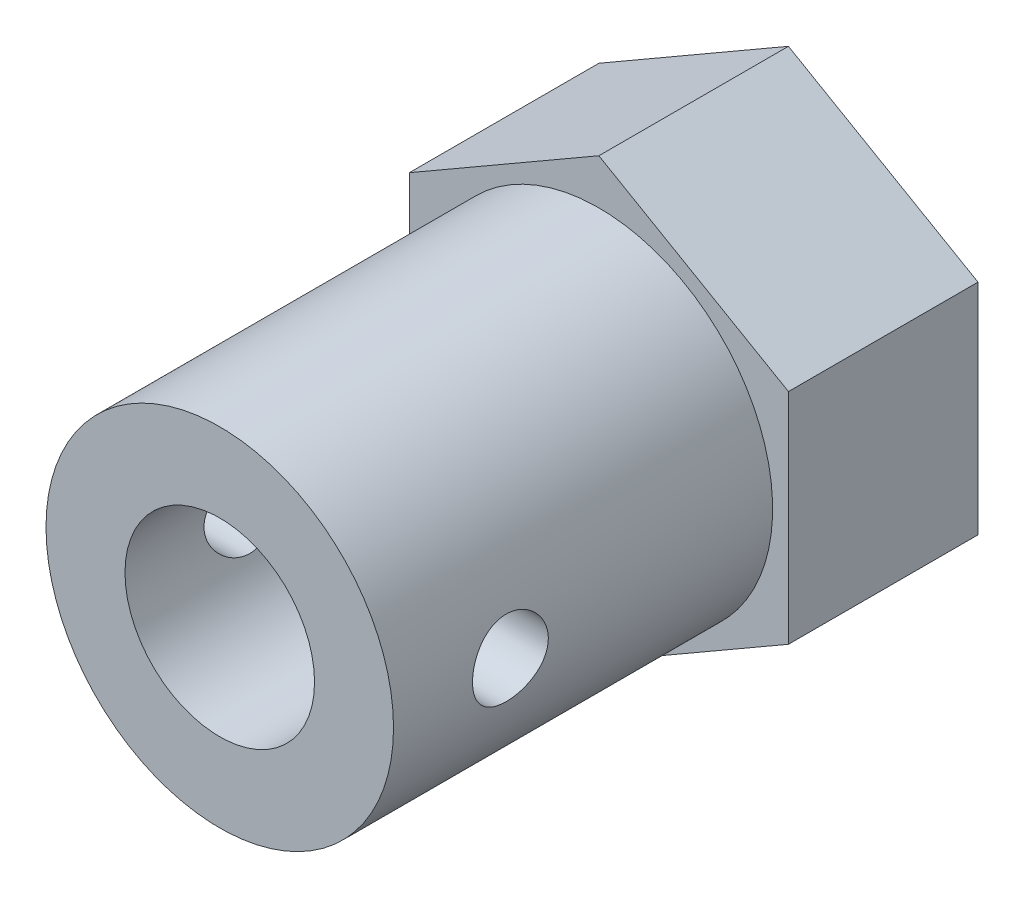
SolidWorks part; units mm, degrees
ref_plane "Plan de face" through (0, 0, 0) normal (0, 0, 1) x (1, 0, 0)
ref_plane "Plan de dessus" through (0, 0, 0) normal (0, 1, 0) x (1, 0, 0)
ref_plane "Plan de droite" through (0, 0, 0) normal (1, 0, 0) x (0, 0, -1)
sketch "Esquisse1" plane through (0, 0, 0) normal (0, 0, 1) x (1, 0, 0)
  circle A0 centre (0, 0) radius 5.5
  dimension "D1" = 11
extrude "Boss.-Extru.1" add sketch "Esquisse1" along normal blind 12
sketch "Esquisse2" plane through (0, 0, 0) normal (0, 0, -1) x (-1, 0, 0)
  line L0 (0, 0) -> (0, 13.8564) construction
  line L1 (6, -3.4641) -> (6, 3.4641)
  line L2 (6, 3.4641) -> (0, 6.9282)
  line L3 (0, 6.9282) -> (-6, 3.4641)
  line L4 (-6, 3.4641) -> (-6, -3.4641)
  line L5 (-6, -3.4641) -> (0, -6.9282)
  line L6 (0, -6.9282) -> (6, -3.4641)
  circle A0 centre (0, 0) radius 6 construction
  point P1 (0, 0)
  dimension "D1" = 12
extrude "Boss.-Extru.2" add sketch "Esquisse2" along normal blind 6
sketch "Esquisse3" plane through (0, 0, 0) normal (1, 0, 0) x (0, 0, -1)
  line L0 (-12, 0) -> (6, 0) construction
  line L1 (6, -3.4641) -> (6, 3.4641) construction
  line L2 (-12, 5.5) -> (-12, -5.5) construction
  line L3 (-8.3, 3.2061) -> (-8.3, -2.7722) construction
  circle A0 centre (-8.3, 0) radius 1.2
  dimension "D2" = 2.4
  dimension "D1" = 14.3
extrude "Enlèv. mat.-Extru.1" cut sketch "Esquisse3" against normal through all and the other way through all
sketch "Esquisse4" plane through (0, 0, 12) normal (0, 0, 1) x (1, 0, 0)
  circle A0 centre (0, 0) radius 3
  dimension "D1" = 6
extrude "Enlèv. mat.-Extru.2" cut sketch "Esquisse4" against normal offset from surface (14 mm away) 4 up to face at (0, 0, -6)
sketch "Esquisse5" plane through (0, 0, -2) normal (0, 0, 1) x (1, 0, 0)
  circle A0 centre (0, 0) radius 1.7
  dimension "D1" = 3.4
extrude "Enlèv. mat.-Extru.3" cut sketch "Esquisse5" against normal through all
